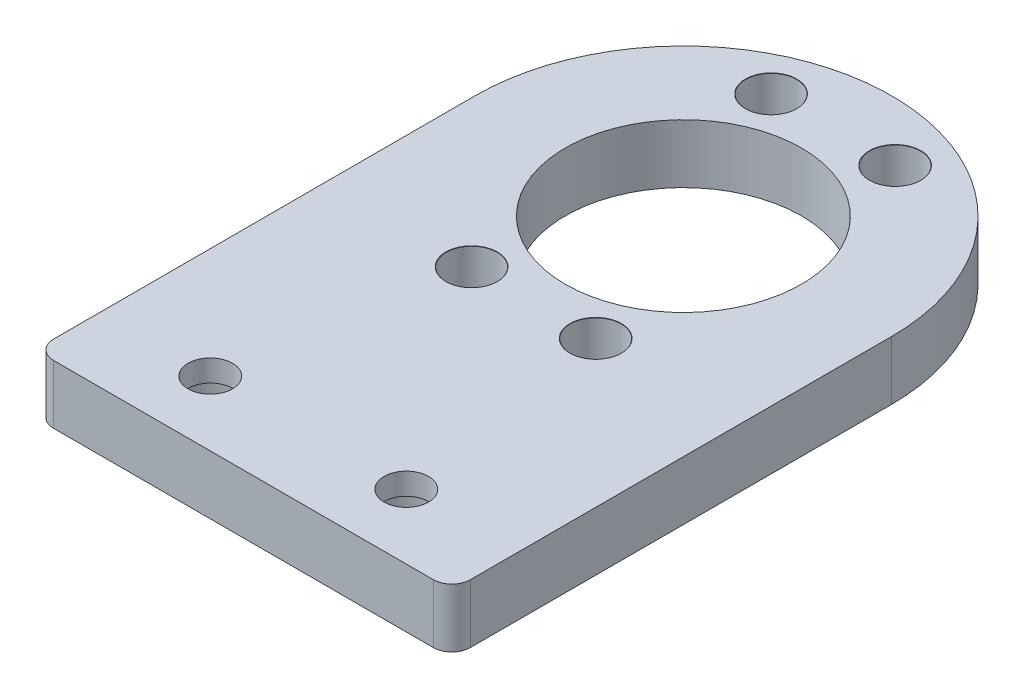
SolidWorks part; units mm, degrees
material "ABS PC"
ref_plane "Front Plane" through (0, 0, 0) normal (0, 0, 1) x (1, 0, 0)
ref_plane "Top Plane" through (0, 0, 0) normal (0, 1, 0) x (1, 0, 0)
ref_plane "Right Plane" through (0, 0, 0) normal (1, 0, 0) x (0, 0, -1)
sketch "Sketch1" plane through (0, 0, 0) normal (0, 1, 0) x (1, 0, 0)
  line L5 (-22.5, -47.5) -> (22.5, -47.5)
  line L6 (-22.5, -47.5) -> (-22.5, 0)
  line L8 (22.5, -47.5) -> (22.5, 0)
  line L9 (-22.5, -47.5) -> (22.5, 0) construction
  line L10 (-22.5, 0) -> (22.5, -47.5) construction
  arc A0 (22.5, 0) -> (-22.5, 0) centre (0, 0) ccw
  point P2 (0, -23.75)
  dimension "D1" = 45
  dimension "D2" = 70
  dimension "D3" = 45
extrude "Boss-Extrude1" add sketch "Sketch1" along normal blind 6.35
sketch "Sketch2" plane through (0, 6.35, 0) normal (0, 1, 0) x (1, 0, 0)
  line L0 (-6.697, 16.1679) -> (6.697, 16.1679) construction
  circle A0 centre (0, 0) radius 17.5 construction
  circle A1 centre (0, 0) radius 17.5 construction
  circle A2 centre (0, 0) radius 17.5 construction
  circle A3 centre (0, 0) radius 17.5 construction
  circle A4 centre (0, 0) radius 17.5 construction
  circle A5 centre (0, 0) radius 17.5 construction
  circle A6 centre (0, 0) radius 17.5 construction
  circle A7 centre (0, 0) radius 17.5 construction
  point P3 (-6.697, 16.1679)
  point P5 (-16.1679, -6.697)
  point P7 (6.697, 16.1679)
  point P9 (16.1679, 6.697)
  point P11 (16.1679, -6.697)
  point P13 (6.697, -16.1679)
  point P15 (-6.697, -16.1679)
  point P16 (0, 0)
  point P18 (-16.1679, 6.697)
  dimension "D1" = 35
  dimension "D2" = 8
hole_wizard "M5 Clearance Hole1" positions "Sketch3" profile "Sketch4" hole size "M5" standard "ANSI Metric" end condition through all
sketch "Sketch3" plane through (0, 6.35, 0) normal (0, 1, 0) x (1, 0, 0)
  point P0 (-6.697, -16.1679)
  point P3 (6.697, -16.1679)
  point P6 (6.697, 16.1679)
  point P15 (-6.697, 16.1679)
sketch "Sketch4" plane through (-6.697, 6.35, 16.1679) normal (1, 0, 0) x (0, 0, 1)
  line L0 (0, 0) -> (0, 6.35)
  line L1 (0, 6.35) -> (2.75, 6.35)
  line L2 (2.75, 6.35) -> (2.75, 0.025)
  line L3 (2.75, 0.025) -> (2.775, 0)
  line L5 (2.775, 0) -> (0, 0)
  line L6 (-2.75, 0.025) -> (-2.775, 0) construction
  line L11 (0, -6.35) -> (0, 107.95) construction
  dimension "Thru Hole Dia." = 5.5
  dimension "Thru Hole Depth" = 6.35
  dimension "Near C'Sink Dia." = 5.55
  dimension "Near C'Sink Angle" = 90
sketch "Sketch5" plane through (0, 6.35, 0) normal (0, 1, 0) x (1, 0, 0)
  circle A0 centre (0, 0) radius 12.75
  dimension "D1" = 25.5
extrude "Cut-Extrude1" cut sketch "Sketch5" against normal through all
sketch "Sketch6" [suppressed] plane through (0, 6.35, 0) normal (0, 1, 0) x (1, 0, 0)
  line L0 (-22.5, -77.5) -> (22.5, -77.5) construction
  circle A0 centre (0, -71) radius 3.3782
  dimension "D1" = 6.7564
  dimension "D2" = 6.5
sketch "Sketch7" [suppressed] plane through (0, 6.35, 0) normal (0, 1, 0) x (1, 0, 0)
  line L0 (12.5, -58.5) -> (-12.5, -58.5) construction
  line L1 (12.5, -63) -> (-12.5, -63)
  line L2 (12.5, -54) -> (-12.5, -54)
  line L3 (0, -71) -> (0, 0) construction
  line L4 (12.5, -42.5) -> (-12.5, -42.5) construction
  line L5 (12.5, -47) -> (-12.5, -47)
  line L6 (12.5, -38) -> (-12.5, -38)
  line L7 (12.5, -26.5) -> (-12.5, -26.5) construction
  line L8 (12.5, -31) -> (-12.5, -31)
  line L9 (12.5, -22) -> (-12.5, -22)
  arc A0 (12.5, -63) -> (12.5, -54) centre (12.5, -58.5) ccw
  arc A1 (-12.5, -54) -> (-12.5, -63) centre (-12.5, -58.5) ccw
  arc A2 (12.5, -47) -> (12.5, -38) centre (12.5, -42.5) ccw
  arc A3 (-12.5, -38) -> (-12.5, -47) centre (-12.5, -42.5) ccw
  arc A4 (12.5, -31) -> (12.5, -22) centre (12.5, -26.5) ccw
  arc A5 (-12.5, -22) -> (-12.5, -31) centre (-12.5, -26.5) ccw
  circle A6 centre (0, -71) radius 3.3782 construction
  point P2 (0, -58.5)
  point P15 (0, -42.5)
  point P22 (0, -26.5)
  point P28 (0, -63)
  dimension "D2" = 4.5
  dimension "D4" = 8
  dimension "D3" = 25
  dimension "D1" = 3
extrude "Cut-Extrude3" [suppressed] cut sketch "Sketch7" against normal through all
sketch "Sketch8" plane through (0, 0, 0) normal (0, -1, 0) x (1, 0, 0)
  line L0 (10.5848, 40.5) -> (-10.5848, 40.5) construction
  line L1 (-22.5, 47.5) -> (22.5, 47.5) construction
  point P2 (0, 40.5)
  point P5 (0, 47.5)
  dimension "D1" = 7
hole_wizard "CBORE for M4 SHCS1" positions "Sketch9" profile "Sketch10" counterbore size "M4" standard "ANSI Metric" end condition through all
sketch "Sketch9" plane through (0, 0, 0) normal (0, -1, 0) x (-1, 0, 0)
  point P0 (-10.5848, -40.5)
  point P3 (10.5848, -40.5)
sketch "Sketch10" plane through (10.5848, 0, 40.5) normal (1, 0, 0) x (0, 0, -1)
  line L0 (0, 0) -> (0, 6.35)
  line L1 (0, 6.35) -> (2.4, 6.35)
  line L3 (2.4, 6.35) -> (2.4, 4)
  line L4 (4, 4) -> (2.4, 4)
  line L5 (4, 4) -> (4, 0.025)
  line L6 (4, 0.025) -> (4.025, 0)
  line L7 (4.025, 0) -> (0, 0)
  line L8 (-4, 0.025) -> (-4.025, 0) construction
  line L11 (0, -6.35) -> (0, 107.95) construction
  dimension "Thru Hole Dia." = 4.8
  dimension "Thru Hole Depth" = 6.35
  dimension "C'Bore Dia." = 8
  dimension "C'Bore Depth" = 4
  dimension "Near C'Sink Dia." = 8.05
  dimension "Near C'Sink Angle" = 90
fillet "Fillet1" radius 2 2 edges at (-22.5, 3.175, 47.5) (22.5, 3.175, 47.5)
